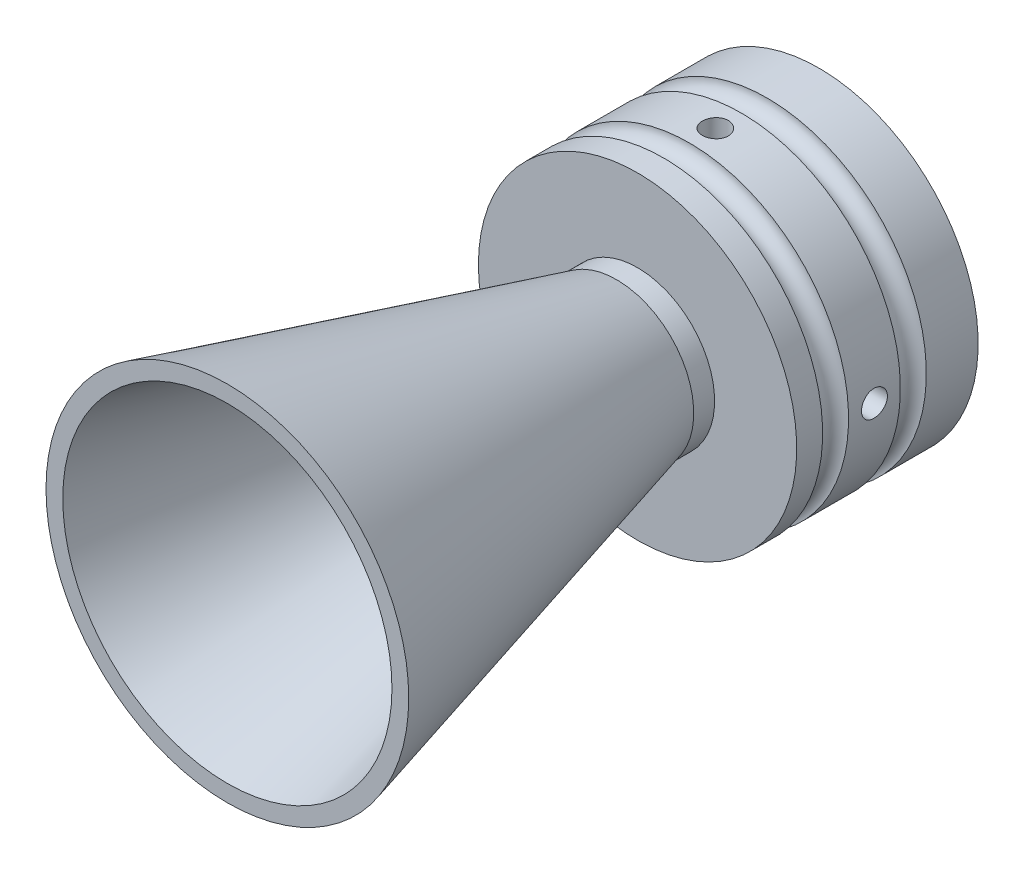
SolidWorks part; units mm, degrees
material "Stainless Steel (ferritic)"
ref_plane "Front Plane" through (0, 0, 0) normal (0, 0, 1) x (1, 0, 0)
ref_plane "Top Plane" through (0, 0, 0) normal (0, 1, 0) x (1, 0, 0)
ref_plane "Right Plane" through (0, 0, 0) normal (1, 0, 0) x (0, 0, -1)
sketch "Sketch1" plane through (0, 0, 0) normal (0, 1, 0) x (1, 0, 0)
  line L0 (24.5618, 27.1444) -> (8.89, 0)
  line L1 (8.89, 0) -> (8.89, -2.54)
  line L2 (8.89, -2.54) -> (25.4, -64.1562)
  line L3 (0, 75.3084) -> (0, -95.0864) construction
  line L6 (11.89, -4.0769) -> (27.9882, -64.1562)
  line L8 (26.7269, 25.8944) -> (11.39, -0.6699) construction
  line L9 (25.4, -64.1562) -> (27.9882, -64.1562)
  line L10 (11.39, -2.2109) -> (27.8148, -63.5091) construction
  line L12 (24.5618, -0.8556) -> (24.5618, 3.1444)
  line L13 (24.5618, 19.1444) -> (24.5618, 27.1444)
  line L14 (11.39, -0.6699) -> (11.39, -2.2109) construction
  line L16 (11.89, -0.8556) -> (24.5618, -0.8556)
  line L17 (24.5618, 15.1444) -> (24.5618, 7.1444)
  line L18 (11.89, -0.8556) -> (11.89, -4.0769)
  arc A2 (24.5618, 19.1444) -> (24.5618, 15.1444) centre (24.5618, 17.1444) ccw
  arc A3 (24.5618, 7.1444) -> (24.5618, 3.1444) centre (24.5618, 5.1444) ccw
  point P9 (8.89, -1.27)
  dimension "D8" = 4
  dimension "D9" = 8
  dimension "D11" = 4
  dimension "D12" = 4
  dimension "D1" = 15
  dimension "D2" = 2.54
  dimension "D3" = 30
  dimension "D4" = 8.89
  dimension "D5" = 25.4
  dimension "D6" = 24.5618
  dimension "D10" = 28
  dimension "D13" = 3
  dimension "D7" = 2.5
revolve "Revolve2" add sketch "Sketch1" angle 360 about L3
ref_plane "Plane3" through (0, 0, -15.1444) normal (0, 0, 1) x (1, 0, 0)
ref_plane "Plane2" through (0, 0, -11.1444) normal (0, 0, 1) x (1, 0, 0)
hole_wizard "Ø4.0mm Dowel Hole1" positions "3DSketch1" profile "Sketch2" hole size "Ø4.0" standard "ISO"
sketch3d "3DSketch1"
  line L0 (0, 24.5618, -11.1444) -> (0, -24.5618, -11.1444)
  line L2 (-24.5618, 0, -11.1444) -> (24.5618, 0, -11.1444)
  point P0 (0, 0, 0)
  point P3 (0, 0, 0)
  point P5 (0, 24.5618, -11.1444)
  point P7 (24.5618, 0, -11.1444)
  point P9 (0, -24.5618, -11.1444)
  point P11 (-24.5618, 0, -11.1444)
  dimension "D1" = 0
sketch "Sketch2" plane through (-24.5618, 0, -11.1444) normal (0, 1, 0) x (0, 0, 1)
  line L0 (0, 0) -> (0, 6.2017)
  line L1 (0, 6.2017) -> (2, 5)
  line L2 (2, 5) -> (2, 0)
  line L5 (2, 0) -> (0, 0)
  line L10 (0, 6.2017) -> (-2, 5) construction
  line L11 (0, -6.35) -> (0, 107.95) construction
  dimension "Hole Dia." = 4
  dimension "Hole Depth" = 5
  dimension "Drill Angle" = 118
ref_plane "Plane4" through (0, 0, -27.1444) normal (0, 0, 1) x (1, 0, 0)
